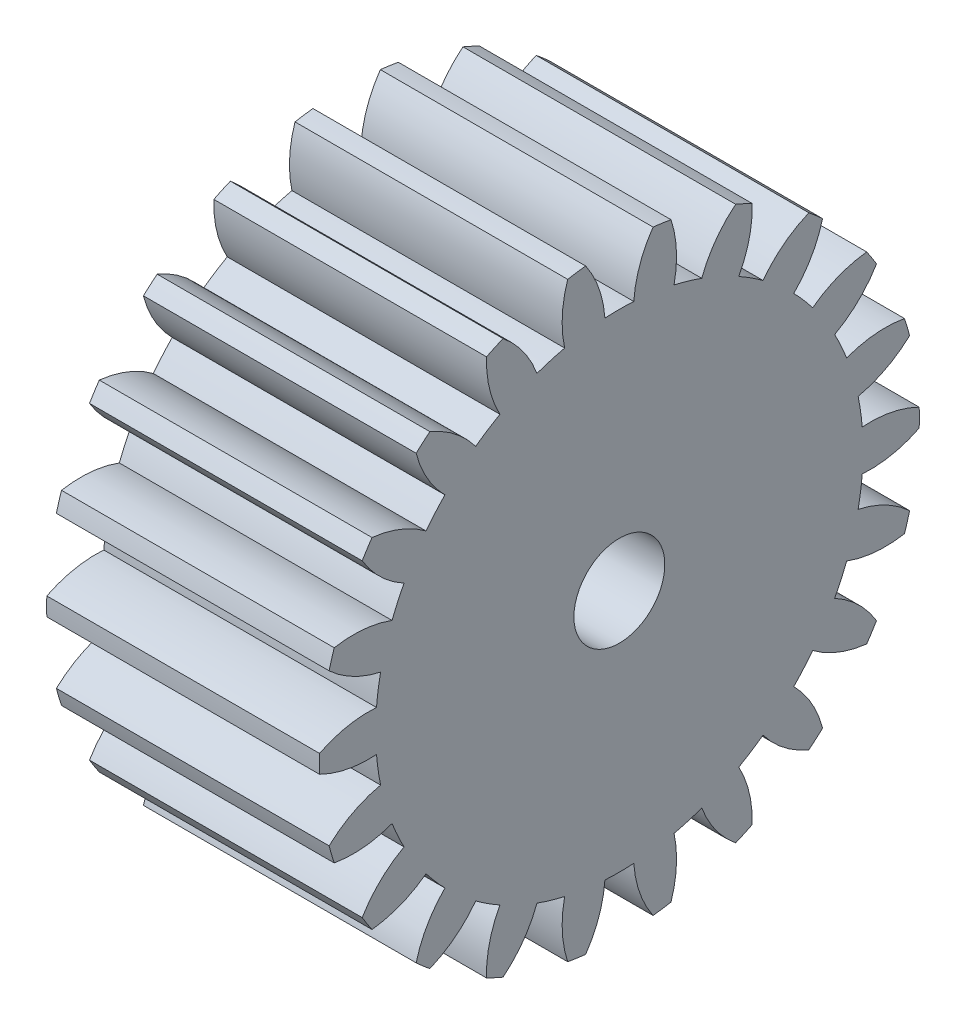
SolidWorks part; units mm, degrees
ref_plane "Plane1" through (0, 0, 0) normal (0, 0, 1) x (1, 0, 0)
ref_plane "Plane2" through (0, 0, 0) normal (0, 1, 0) x (1, 0, 0)
ref_plane "Plane3" through (0, 0, 0) normal (1, 0, 0) x (0, 0, -1)
sketch "HoldingSke" plane through (0, 0, 0) normal (0, 1, 0) x (1, 0, 0)
  line L0 (0, 0) -> (0.6743, -0.2724)
  line L1 (-15, 0) -> (100, 0) construction
  line L2 (0, 0) -> (-2.1039, 2.3779)
  line L3 (0, 0) -> (-11.863, 4.5341)
  line L4 (0, 0) -> (8.0072, 3.2351)
  line L5 (0, 0) -> (-46.8476, -17.4728)
  line L6 (0, 0) -> (-12.4344, -8.3896)
  line L7 (-2.1039, 2.3779) -> (8.6586, 51.2059)
  line L8 (-76.2, 54.61) -> (-75.3, 54.61)
  line L9 (-67.7845, 28.3722) -> (-49.3413, 33.142)
  line L10 (-76.2, 71.12) -> (104.1128, 71.12)
  line L11 (0, 0) -> (-15, 0)
  line L12 (-76.2, 101.6) -> (-76.151, 101.6)
  line L13 (24.9733, 27.94) -> (52.9518, 28.4284)
  line L14 (24.9733, 27.94) -> (24.9743, 27.94)
  line L15 (24.9733, 27.94) -> (100.4006, 29.5858)
  line L16 (-63.627, -1.375) -> (-12.827, -1.375)
  circle A0 centre (0, 0) radius 2.5
  circle A1 centre (0, 0) radius 13.4053
  circle A2 centre (0, 0) radius 37.5
  circle A3 centre (0, 0) radius 2.5
  dimension "MHD" = 26.8105
  dimension "Hub_dia" = 75
  dimension "Bore" = 5
  dimension "MBD" = 5
  dimension "Num_teeth" = 22
  dimension "Pitch" = 0.7273
  dimension "Overall_len" = 50
  dimension "Show_teeth" = 22
  dimension "Thickness" = 15
  dimension "OAL" = 50.0001
  dimension "T_dim" = 0.9
  dimension "Ap" = 14.5
  dimension "H" = 19.05
  dimension "Pitch_radius" = 180.3128
  dimension "Width" = 15
  dimension "Backlash" = 0.049
  dimension "Addendum_fac" = 1
  dimension "Dedendum_fac" = 1.25
  dimension "Clearance_fac" = 0.25
  dimension "Dedendum_add" = 0.001
  dimension "Module" = 1.375
sketch "BasProSke" plane through (0, 0, 0) normal (0, 1, 0) x (1, 0, 0)
  line L0 (-10, 0) -> (60, 0) construction
  line L1 (0, 0) -> (0, 16.5)
  line L2 (0, 0) -> (15, 0)
  line L3 (15, 0) -> (15, 16.5)
  line L4 (15, 16.5) -> (0, 16.5)
  dimension "Thickness" = 15
  dimension "Diameter" = 33
revolve "Base-Revolve" add sketch "BasProSke" angle 360 about L0
sketch "TooCutSke" plane through (0, 0, 0) normal (1, 0, 0) x (0, 0, -1)
  line L1 (0, 0) -> (0, 107) construction
  line L2 (0, 0) -> (-1.1647, 15.0801) construction
  line L3 (0, 0) -> (-4.2957, 29.8775) construction
  line L4 (-1.1647, 15.0801) -> (-2.1479, 14.9387) construction
  arc A0 (0.7938, 13.3817) -> (-0.7938, 13.3817) centre (0, 0) ccw
  arc A1 (1.8697, 16.4193) -> (-1.8697, 16.4193) centre (0, 0) ccw
  circle A2 centre (0, 0) radius 15.125 construction
  circle A3 centre (0, 0) radius 14.6432 construction
  arc A4 (-0.7938, 13.3817) -> (-1.8697, 16.4193) centre (-6.8287, 12.9535) ccw
  arc A5 (1.8697, 16.4193) -> (0.7938, 13.3817) centre (6.8287, 12.9535) ccw
  dimension "Root_dia" = 26.8105
  dimension "Overcut_dia" = 33.0508
  dimension "Pitch_dia" = 30.25
  dimension "Base_dia" = 29.2865
  dimension "Flank_rad" = 6.05
  dimension "Half_ang" = 8.182
  dimension "Half_CT" = 0.9933
extrude "ToothCut" cut sketch "TooCutSke" along normal through all
fillet "Breaks" [suppressed] radius 0.0275
fillet "RootFillets" [suppressed] radius 0.3448
pattern_circular "TeethCuts" count 22 over 360 about axis through (0, 0, 0) along (1, 0, 0) of "ToothCut", "RootFillets", "Breaks"
sketch "HubNeaOneSke" plane through (0, 0, 0) normal (-1, 0, 0) x (0, 0, 1)
  circle A0 centre (0, 0) radius 13.4053
  dimension "Diameter" = 26.8105
extrude "HubNearOne" [suppressed] add sketch "HubNeaOneSke" along normal blind 35.0001
sketch "HubNeaBotSke" plane through (0, 0, 0) normal (-1, 0, 0) x (0, 0, 1)
  circle A0 centre (0, 0) radius 13.4053
  dimension "Diameter" = 26.8105
extrude "HubNearBoth" [suppressed] add sketch "HubNeaBotSke" along normal blind 17.5
ref_plane "FarPln" through (15, 0, 0) normal (1, 0, 0) x (0, 0, -1)
sketch "HubFarSke" plane through (15, 0, 0) normal (1, 0, 0) x (0, 0, -1)
  circle A0 centre (0, 0) radius 13.4053
  dimension "Diameter" = 26.8105
extrude "HubFar" [suppressed] add sketch "HubFarSke" along normal blind 17.5
sketch "BorSke" plane through (0, 0, 0) normal (1, 0, 0) x (0, 0, -1)
  circle A0 centre (0, 0) radius 2.5
  dimension "Diameter" = 5
extrude "Bore" cut sketch "BorSke" along normal mid plane 100.0001
sketch "KeySke" plane through (0, 0, 0) normal (1, 0, 0) x (0, 0, -1)
  line L0 (-1, 0) -> (-1, 3.4)
  line L1 (-1, 3.4) -> (1, 3.4)
  line L2 (1, 3.4) -> (1, 0)
  line L3 (0, 0) -> (0, 34) construction
  line L4 (-1, 0) -> (1, 0)
  dimension "Offset" = 3.4
  dimension "Width" = 2
extrude "Keyway" [suppressed] cut sketch "KeySke" along normal mid plane 100.0001
pattern_circular "Keyway2" [suppressed] count 2 every 90 about axis through (-10, 0, 0) along (1, 0, 0)
equation "' \"Module@HoldingSke\" = 6.35"
equation "' \"Num_teeth@HoldingSke\" = 12"
equation "' \"Ap@HoldingSke\" =  20"
equation "' \"Ap@HoldingSke\" = 20"
equation "' \"Width@HoldingSke\" = 0.5 * 25.4"
equation "' \"Hub_dia@HoldingSke\"= 1 * 25.4"
equation "' \"Hub_dia@HoldingSke\" = 1 * 25.4"
equation "' \"Overall_len@HoldingSke\" = 1.0 * 25.4"
equation "' \"Bore@HoldingSke\" = 0.75 * 25.4"
equation "' \"T_dim@HoldingSke\" = 0.1 * 25.4"
equation "' \"Width@KeySke\" = 0.25 * 25.4"
equation "' \"Show_teeth@HoldingSke\" = 13"
equation "' \"Backlash@HoldingSke\" = 0.009 * 25.4"
equation "' \"Addendum_fac@HoldingSke\" = 1.0"
equation "' \"Dedendum_fac@HoldingSke\" = 1.25"
equation "' \"Dedendum_add@HoldingSke\" = 0.00005 * 25.4"
equation "' \"Clearance_fac@HoldingSke\" = 0.25"
equation "\"Pitch@HoldingSke\" = 1 / \"Module@HoldingSke\""
equation "\"Overcut_dia@TooCutSke\" = (\"Num_teeth@HoldingSke\" + 2 * \"Addendum_fac@HoldingSke\") / \"Pitch@HoldingSke\" + 0.002 * 25.4"
equation "\"Pitch_dia@TooCutSke\" = \"Num_teeth@HoldingSke\" / \"Pitch@HoldingSke\""
equation "\"Base_dia@TooCutSke\" = \"Num_teeth@HoldingSke\" / \"Pitch@HoldingSke\" * cos((\"Ap@HoldingSke\"  * 3.14159265 / 180))"
equation "\"Root_dia@TooCutSke\" = (\"Num_teeth@HoldingSke\" + 2) / \"Pitch@HoldingSke\" - 2 * (\"Addendum_fac@HoldingSke\" + \"Dedendum_fac@HoldingSke\") / \"Pitch@HoldingSke\" - \"Dedendum_add@HoldingSke\" * 2"
equation "\"Half_ang@TooCutSke\" = 180 / \"Num_teeth@HoldingSke\""
equation "\"Half_CT@TooCutSke\" = \"Num_teeth@HoldingSke\" / \"Pitch@HoldingSke\" * sin((3.14159265 / 2 / \"Num_teeth@HoldingSke\")) / 2 - 7 * \"Backlash@HoldingSke\" / 4"
equation "\"Flank_rad@TooCutSke\" = \"Num_teeth@HoldingSke\" / \"Pitch@HoldingSke\" / 5"
equation "\"Radius@RootFillets\" = \"Clearance_fac@HoldingSke\" / \"Pitch@HoldingSke\" + \"Dedendum_add@HoldingSke\""
equation "\"Break_rad@Breaks\" = 0.02 / \"Pitch@HoldingSke\""
equation "\"Thickness@HoldingSke\" = \"Width@HoldingSke\""
equation "\"OAL@HoldingSke\" = \"Thickness@HoldingSke\""
equation "\"MHD@HoldingSke\" = (\"Num_teeth@HoldingSke\" + 2) / \"Pitch@HoldingSke\" - 2 * (\"Addendum_fac@HoldingSke\" + \"Dedendum_fac@HoldingSke\")  / \"Pitch@HoldingSke\" - \"Dedendum_add@HoldingSke\" * 2"
equation "\"MBD@HoldingSke\" = (\"Num_teeth@HoldingSke\" + 2) / \"Pitch@HoldingSke\" - 2 * (\"Addendum_fac@HoldingSke\" + \"Dedendum_fac@HoldingSke\")  / \"Pitch@HoldingSke\" - \"Dedendum_add@HoldingSke\" * 2 - 0.002 * 25.4"
equation "\"MHD@HoldingSke\" = ((sgn( \"MHD@HoldingSke\" - \"Hub_dia@HoldingSke\" )-1)*( \"MHD@HoldingSke\" - \"Hub_dia@HoldingSke\" ))/-2+ \"Hub_dia@HoldingSke\""
equation "\"MBD@HoldingSke\" = ((sgn( \"MBD@HoldingSke\" - \"Bore@HoldingSke\" )-1)*( \"MBD@HoldingSke\" - \"Bore@HoldingSke\" ))/-2+ \"Bore@HoldingSke\""
equation "\"OAL@HoldingSke\" = ((sgn( \"OAL@HoldingSke\" - \"Overall_len@HoldingSke\" )+1)*( \"OAL@HoldingSke\" - \"Overall_len@HoldingSke\" ))/2 + \"Overall_len@HoldingSke\" + 0.000002 * 25.4"
equation "\"Num_teeth@TeethCuts\" = int( \"Show_teeth@HoldingSke\" ) + 1"
equation "\"Num_teeth@TeethCuts\" = ((sgn( \"Num_teeth@TeethCuts\" - \"Num_teeth@HoldingSke\" )-1)*( \"Num_teeth@TeethCuts\" - \"Num_teeth@HoldingSke\" ))/-2+ \"Num_teeth@HoldingSke\""
equation "\"Num_teeth@TeethCuts\" = ((sgn( \"Num_teeth@TeethCuts\" - 2.0)+1)*( \"Num_teeth@TeethCuts\" - 2.0))/2 +2.0"
equation "\"Angle@TeethCuts\" = 360.0 / \"Num_teeth@HoldingSke\""
equation "\"Diameter@BasProSke\" = (\"Num_teeth@HoldingSke\" + 2 * \"Addendum_fac@HoldingSke\") / \"Pitch@HoldingSke\""
equation "\"Thickness@BasProSke\"  = \"Thickness@HoldingSke\""
equation "' \"Fillet_rad@BasProSke\" =  \"Thickness@HoldingSke\" * 0.05"
equation "' \"Fillet_rad@BasProSke\" = \"Thickness@HoldingSke\" * 0.05"
equation "\"MHD@HoldingSke\" = ((sgn( \"MHD@HoldingSke\" - \"Root_dia@TooCutSke\" )-1)*( \"MHD@HoldingSke\" - \"Root_dia@TooCutSke\" ))/-2+ \"Root_dia@TooCutSke\""
equation "\"Diameter@HubNeaOneSke\" = \"MHD@HoldingSke\""
equation "\"Length@HubNearOne\" = \"OAL@HoldingSke\" - \"Thickness@BasProSke\""
equation "\"Diameter@HubNeaBotSke\" = \"MHD@HoldingSke\""
equation "\"Length@HubNearBoth\" = ( \"OAL@HoldingSke\" - \"Thickness@BasProSke\" ) / 2.0"
equation "\"Thickness@FarPln\" = \"Thickness@BasProSke\""
equation "\"Diameter@HubFarSke\" = \"MHD@HoldingSke\""
equation "\"Length@HubFar\" = ( \"OAL@HoldingSke\" - \"Thickness@BasProSke\" ) / 2.0"
equation "\"Diameter@BorSke\" = \"MBD@HoldingSke\""
equation "\"D1@Bore\" = \"OAL@HoldingSke\" * 2.0"
equation "\"D1@Keyway\" = \"OAL@HoldingSke\" * 2.0"
equation "\"Offset@KeySke\" = \"T_dim@HoldingSke\" + \"MBD@HoldingSke\" / 2.0"
